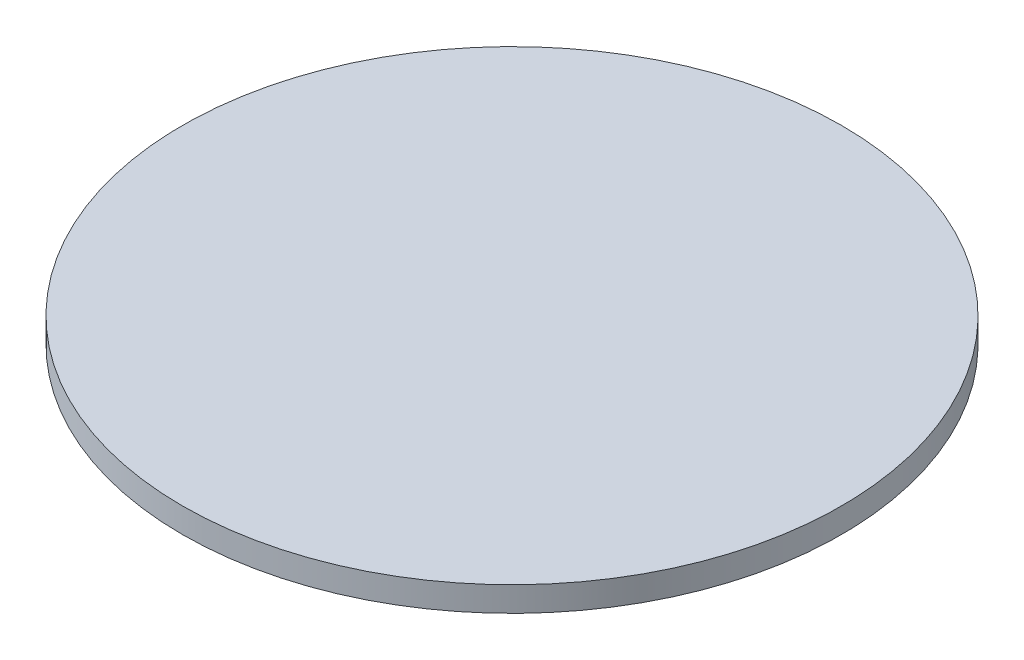
SolidWorks part; units mm, degrees
ref_plane "Front Plane" through (0, 0, 0) normal (0, 0, 1) x (1, 0, 0)
ref_plane "Top Plane" through (0, 0, 0) normal (0, 1, 0) x (1, 0, 0)
ref_plane "Right Plane" through (0, 0, 0) normal (1, 0, 0) x (0, 0, -1)
sketch "Sketch1" plane through (0, 0, 0) normal (0, 1, 0) x (1, 0, 0)
  circle A0 centre (0, 0) radius 42.164
  dimension "D1" = 84.328
extrude "Boss-Extrude1" add sketch "Sketch1" along normal blind 3.175
